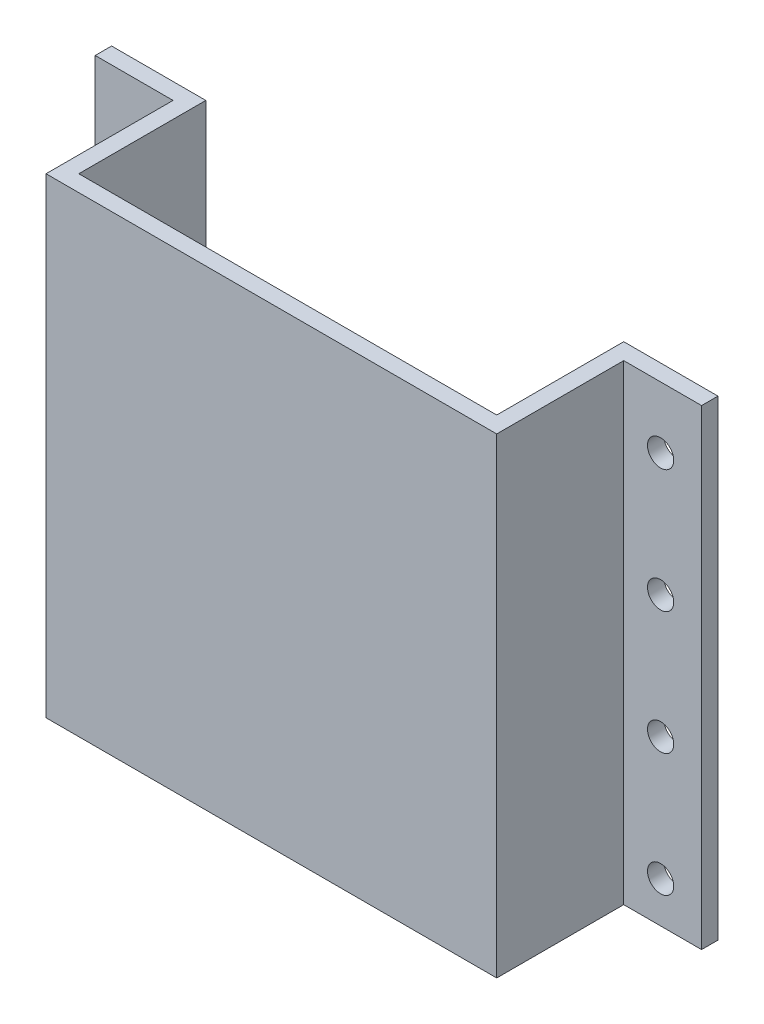
SolidWorks part; units mm, degrees
material "PET"
ref_plane "前视基准面" through (0, 0, 0) normal (0, 0, 1) x (1, 0, 0)
ref_plane "上视基准面" through (0, 0, 0) normal (0, 1, 0) x (1, 0, 0)
ref_plane "右视基准面" through (0, 0, 0) normal (1, 0, 0) x (0, 0, -1)
other "Configuration Table"
sketch "草图1" plane through (0, 0, 0) normal (0, 1, 0) x (1, 0, 0)
  line L0 (-5.048, 0) -> (4.452, 0)
  line L1 (4.452, 0) -> (4.452, -15.5)
  line L2 (4.452, -15.5) -> (59.452, -15.5)
  line L3 (59.452, -15.5) -> (59.452, 0)
  line L4 (59.452, 0) -> (68.952, 0)
  line L5 (68.952, 0) -> (68.952, 2)
  line L6 (68.952, 2) -> (57.452, 2)
  line L7 (57.452, 2) -> (57.452, -13.5)
  line L8 (57.452, -13.5) -> (6.452, -13.5)
  line L9 (6.452, -13.5) -> (6.452, 2)
  line L10 (6.452, 2) -> (-5.048, 2)
  line L11 (-5.048, 2) -> (-5.048, 0)
  dimension "D1" = 15.5
  dimension "D2" = 51
  dimension "D3" = 55
  dimension "D4" = 2
  dimension "D5" = 2
  dimension "D6" = 11.5
  dimension "D7" = 11.5
  dimension "D8" = 2
extrude "凸台-拉伸1" add sketch "草图1" along normal blind 70
sketch "草图2" plane through (0, 0, 0) normal (0, -1, 0) x (1, 0, 0)
  line L1 (6.452, 13.5) -> (57.452, 13.5)
  line L2 (6.452, 13.5) -> (6.452, -2)
  line L3 (6.452, -2) -> (57.452, -2)
  line L4 (57.452, 13.5) -> (57.452, -2)
extrude "凸台-拉伸2" add sketch "草图2" against normal blind 5
sketch "草图3" plane through (0, 0, 0) normal (0, 0, 1) x (1, 0, 0)
  line L2 (-0.048, 35) -> (-5.048, 35) construction
  line L3 (-5.048, 70) -> (-5.048, 0) construction
  line L4 (31.952, 70) -> (31.952, 0) construction
  line L5 (4.452, 70) -> (59.452, 70) construction
  line L6 (4.452, 0) -> (59.452, 0) construction
  line L7 (63.952, 35) -> (68.952, 35) construction
  line L8 (63.952, 70) -> (63.952, 0) construction
  circle A0 centre (-0.048, 35) radius 1.6
  circle A1 centre (-0.048, 20) radius 1.6
  circle A2 centre (-0.048, 5) radius 1.6
  circle A3 centre (-0.048, 65) radius 1.6
  circle A4 centre (-0.048, 50) radius 1.6
  circle A5 centre (63.952, 50) radius 1.6
  circle A6 centre (63.952, 65) radius 1.6
  circle A7 centre (63.952, 5) radius 1.6
  circle A8 centre (63.952, 20) radius 1.6
  circle A9 centre (63.952, 35) radius 1.6
  dimension "D1" = 3.2
  dimension "D4" = 15
  dimension "D3" = 5
  dimension "D2" = 15
extrude "切除-拉伸1" cut sketch "草图3" against normal blind 17
sketch "草图4" plane through (0, 70, 0) normal (0, 1, 0) x (1, 0, 0)
  line L1 (-116.3013, 57.4708) -> (80.5611, 57.4708)
  line L2 (-116.3013, 57.4708) -> (-116.3013, -23.4759)
  line L3 (-116.3013, -23.4759) -> (80.5611, -23.4759)
  line L4 (80.5611, 57.4708) -> (80.5611, -23.4759)
  line L5 (-116.3013, 57.4708) -> (80.5611, -23.4759) construction
  line L6 (-116.3013, -23.4759) -> (80.5611, 57.4708) construction
  point P0 (-17.8701, 16.9975)
extrude "切除-拉伸2" cut sketch "草图4" against normal blind 12.5
